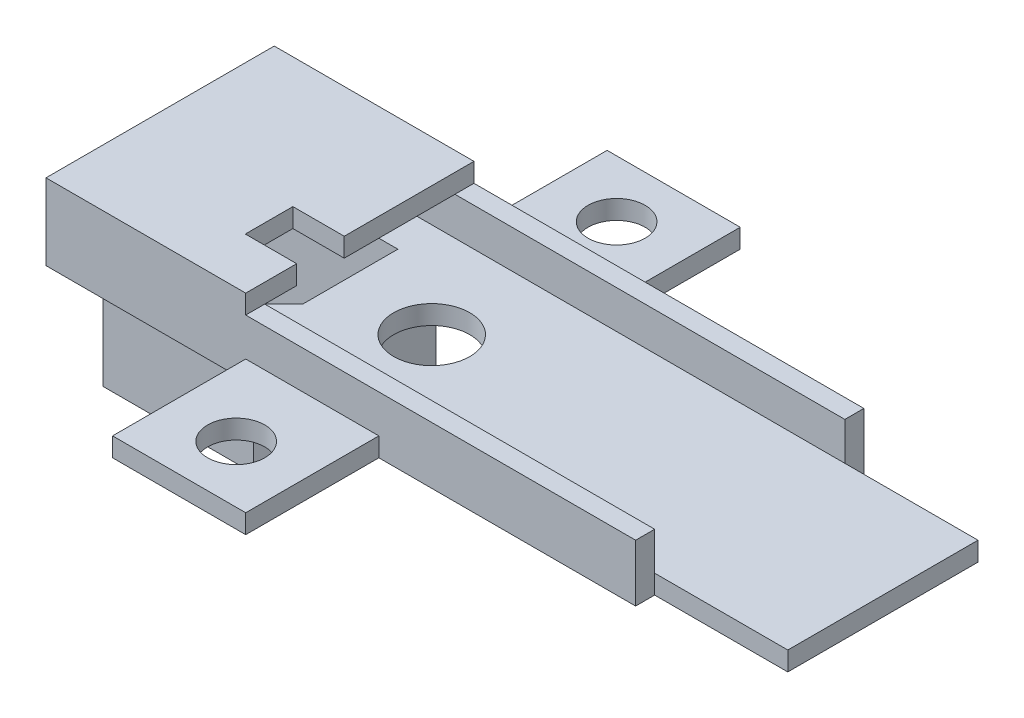
SolidWorks part; units mm, degrees
ref_plane "前视基准面" through (0, 0, 0) normal (0, 0, 1) x (1, 0, 0)
ref_plane "上视基准面" through (0, 0, 0) normal (0, 1, 0) x (1, 0, 0)
ref_plane "右视基准面" through (0, 0, 0) normal (1, 0, 0) x (0, 0, -1)
sketch "草图1" plane through (0, 0, 0) normal (0, 1, 0) x (1, 0, 0)
  line L0 (-12.5242, -6.4845) -> (-12.5242, -12.4845)
  line L1 (-13.5242, -4.4845) -> (-4.0242, -4.4845) construction
  line L2 (-13.5242, -4.4845) -> (-13.5242, -14.4845) construction
  line L3 (-13.5242, -14.4845) -> (-4.0242, -14.4845) construction
  line L4 (23.4758, -4.4845) -> (23.4758, -14.4845)
  line L5 (-12.5242, -12.4845) -> (-6.0242, -12.4845)
  line L6 (-5.0242, -11.4845) -> (-5.0242, -6.4845)
  line L7 (-5.0242, -6.4845) -> (-12.5242, -6.4845)
  line L8 (-6.0242, -12.4845) -> (-5.0242, -11.4845)
  line L9 (-53.0418, -9.4845) -> (30.158, -9.4845) construction
  line L10 (-4.0242, -3.4845) -> (-4.0242, 3.5155)
  line L11 (-4.0242, 3.5155) -> (2.9758, 3.5155)
  line L12 (2.9758, 3.5155) -> (2.9758, -3.4845)
  line L13 (3.9758, -4.4845) -> (23.4758, -4.4845) construction
  line L14 (-4.0242, -15.4845) -> (-4.0242, -22.4845)
  line L15 (2.9758, -22.4845) -> (2.9758, -15.4845)
  line L16 (-4.0242, -22.4845) -> (2.9758, -22.4845)
  line L17 (3.9758, -14.4845) -> (23.4758, -14.4845) construction
  line L18 (-4.0242, -3.4845) -> (-14.5242, -3.4845)
  line L19 (-14.5242, -3.4845) -> (-14.5242, -15.4845)
  line L20 (-14.5242, -15.4845) -> (-4.0242, -15.4845)
  line L21 (2.9758, -3.4845) -> (16.4758, -3.4845)
  line L22 (16.4758, -3.4845) -> (16.4758, -4.4845)
  line L23 (16.4758, -15.4845) -> (16.4758, -14.4845)
  line L24 (2.9758, -15.4845) -> (16.4758, -15.4845)
  line L25 (16.4758, -4.4845) -> (23.4758, -4.4845)
  line L26 (23.4758, -14.4845) -> (16.4758, -14.4845)
  point P12 (23.4758, -9.4845)
  dimension "D1" = 37
  dimension "D2" = 10
  dimension "D3" = 6
  dimension "D4" = 2
  dimension "D5" = 7.5
  dimension "D6" = 135
  dimension "D7" = 1
  dimension "D8" = 5
  dimension "D9" = 1
  dimension "D10" = 1
  dimension "D11" = 1
  dimension "D12" = 1
  dimension "D13" = 7
  dimension "D14" = 12.5
  dimension "D15" = 7
extrude "凸台-拉伸1" add sketch "草图1" along normal blind 1
sketch "草图2" plane through (0, 0, 0) normal (0, -1, 0) x (1, 0, 0)
  line L0 (-12.5242, 12.4845) -> (-6.0242, 12.4845)
  line L1 (-12.5242, 12.4845) -> (-6.0242, 12.4845) construction
  line L2 (-6.0242, 12.4845) -> (-5.0242, 11.4845) construction
  line L3 (-6.0242, 12.4845) -> (-5.0242, 11.4845)
  line L4 (-5.0242, 11.4845) -> (-5.0242, 6.4845)
  line L5 (-5.0242, 6.4845) -> (-12.5242, 6.4845)
  line L6 (-12.5242, 6.4845) -> (-12.5242, 12.4845)
  line L7 (-13.5242, 5.4845) -> (-13.5242, 13.4845)
  line L8 (-13.5242, 13.4845) -> (-5.61, 13.4845)
  line L9 (-5.61, 13.4845) -> (-4.0242, 11.8987)
  line L10 (-4.0242, 11.8987) -> (-4.0242, 5.4845)
  line L11 (-4.0242, 5.4845) -> (-13.5242, 5.4845)
  dimension "D1" = 1
extrude "凸台-拉伸2" add sketch "草图2" along normal blind 6
sketch "草图3" plane through (0, 1, 0) normal (0, 1, 0) x (1, 0, 0)
  line L1 (-18.2722, -9.4845) -> (28.1646, -9.4845) construction
  line L2 (-14.5242, -3.4845) -> (-14.5242, -15.4845) construction
  circle A0 centre (-0.2442, -9.4845) radius 2
  point P6 (0, 0)
  dimension "D1" = 4
  dimension "D2" = 14.28
extrude "切除-拉伸1" cut sketch "草图3" against normal blind 1
sketch "草图4" plane through (0, 1, 0) normal (0, 1, 0) x (1, 0, 0)
  line L0 (-14.5242, -3.4845) -> (16.4758, -3.4845)
  line L1 (16.4758, -3.4845) -> (16.4758, -4.4845)
  line L2 (16.4758, -4.4845) -> (-13.5242, -4.4845)
  line L3 (-14.5242, -3.4845) -> (-14.5242, -15.4845)
  line L4 (-14.5242, -15.4845) -> (16.4758, -15.4845)
  line L5 (16.4758, -15.4845) -> (16.4758, -14.4845)
  line L6 (16.4758, -14.4845) -> (-13.5242, -14.4845)
  line L7 (-13.5242, -14.4845) -> (-13.5242, -4.4845)
  dimension "D1" = 1
extrude "凸台-拉伸3" add sketch "草图4" along normal blind 2
sketch "草图5" plane through (0, 3, 0) normal (0, 1, 0) x (1, 0, 0)
  line L0 (-14.5242, -3.4845) -> (-14.5242, -15.4845)
  line L1 (-14.5242, -15.4845) -> (-4.0242, -15.4845)
  line L2 (-14.5242, -15.4845) -> (16.4758, -15.4845) construction
  line L3 (-14.5242, -3.4845) -> (-4.0242, -3.4845)
  line L4 (16.4758, -3.4845) -> (-14.5242, -3.4845) construction
  line L5 (-4.0242, -3.4845) -> (-4.0242, -10.3045)
  line L6 (-6.7242, -10.3045) -> (-6.7242, -12.8045)
  line L7 (-6.7242, -12.8045) -> (-4.0242, -12.8045)
  line L9 (-4.0242, -10.3045) -> (-6.7242, -10.3045)
  line L10 (-4.0242, -12.8045) -> (-4.0242, -15.4845)
  point P12 (-5.7242, -3.4845)
  dimension "D1" = 7.8
  dimension "D2" = 2.68
  dimension "D3" = 2.5
  dimension "D4" = 2.7
extrude "凸台-拉伸4" add sketch "草图5" along normal blind 1
sketch "草图6" plane through (0, 1, 0) normal (0, 1, 0) x (1, 0, 0)
  line L0 (-0.5242, -25.7028) -> (-0.5242, 5.5341) construction
  line L1 (2.9758, 3.5155) -> (-4.0242, 3.5155) construction
  line L2 (-17.6881, -9.4845) -> (25.119, -9.4845) construction
  circle A0 centre (-0.5242, 0.5155) radius 1.5
  circle A1 centre (-0.5242, -19.4845) radius 1.5
  dimension "D1" = 3
  dimension "D2" = 3
extrude "切除-拉伸2" cut sketch "草图6" against normal blind 1
